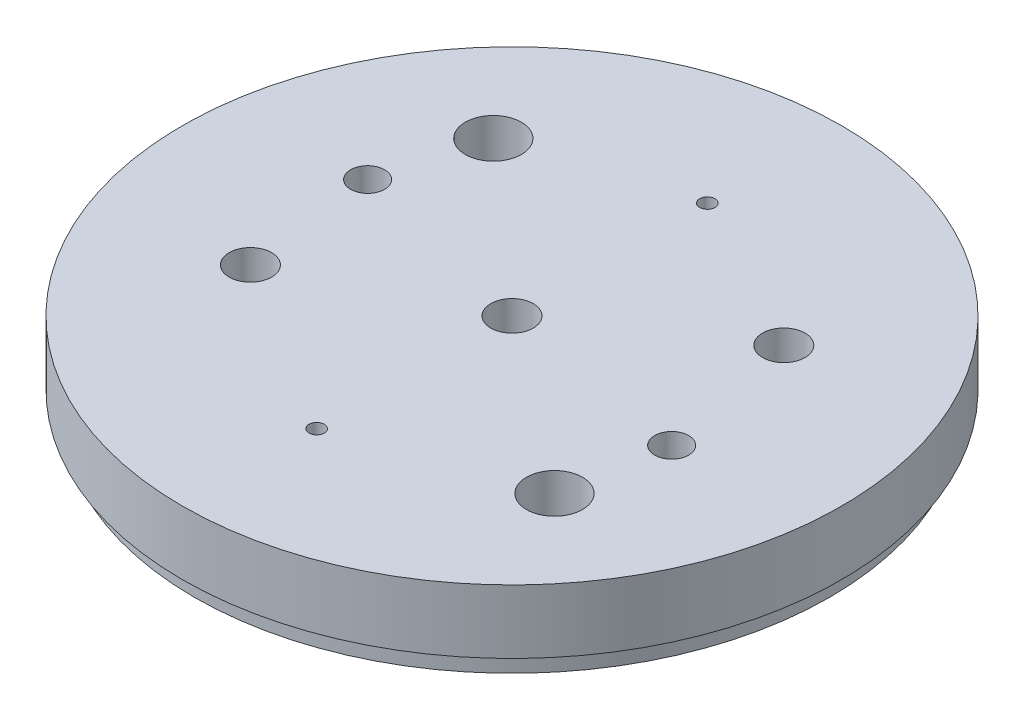
SolidWorks part; units mm, degrees
material "Gray Cast Iron"
ref_plane "Front Plane" through (0, 0, 0) normal (0, 0, 1) x (1, 0, 0)
ref_plane "Top Plane" through (0, 0, 0) normal (0, 1, 0) x (1, 0, 0)
ref_plane "Right Plane" through (0, 0, 0) normal (1, 0, 0) x (0, 0, -1)
sketch "Sketch1" plane through (0, 0, 0) normal (0, 1, 0) x (1, 0, 0)
  circle A0 centre (0, 0) radius 49.276
  dimension "D1" = 98.552
extrude "Boss-Extrude1" add sketch "Sketch1" against normal blind 9.525
sketch "Sketch2" plane through (0, -9.525, 0) normal (0, -1, 0) x (1, 0, 0)
  circle A0 centre (0, 0) radius 47.498
  dimension "D1" = 94.996
extrude "Boss-Extrude2" add sketch "Sketch2" along normal blind 3.175
sketch "Sketch5" plane through (0, 0, 0) normal (0, 1, 0) x (1, 0, 0)
  line L0 (0, 0) -> (58.6469, 0) construction
  line L1 (0, 0) -> (0, -17.1488) construction
  circle A0 centre (0, 0) radius 3.175
  circle A1 centre (0, 29.21) radius 1.143
  circle A2 centre (0, -29.21) radius 1.143
  circle A3 centre (-24.384, 21.59) radius 4.191
  circle A4 centre (-28.448, 6.858) radius 2.54
  circle A5 centre (-26.162, -12.954) radius 3.175
  circle A6 centre (26.162, -19.812) radius 4.191
  circle A7 centre (28.702, -4.826) radius 2.54
  circle A8 centre (24.13, 16.51) radius 3.175
  dimension "D1" = 6.35
  dimension "D2" = 2.286
  dimension "D3" = 2.286
  dimension "D4" = 6.35
  dimension "D5" = 6.35
  dimension "D7" = 29.21
  dimension "D8" = 16.51
  dimension "D12" = 8.382
  dimension "D13" = 5.08
  dimension "D14" = 8.382
  dimension "D15" = 5.08
  dimension "D16" = 4.826
  dimension "D19" = 19.812
  dimension "D20" = 6.858
  dimension "D22" = 24.384
  dimension "D6" = 29.21
  dimension "D9" = 24.13
  dimension "D10" = 12.954
  dimension "D11" = 26.162
  dimension "D17" = 28.702
  dimension "D18" = 26.162
  dimension "D21" = 28.448
  dimension "D23" = 21.59
extrude "Cut-Extrude1" cut sketch "Sketch5" against normal through all
